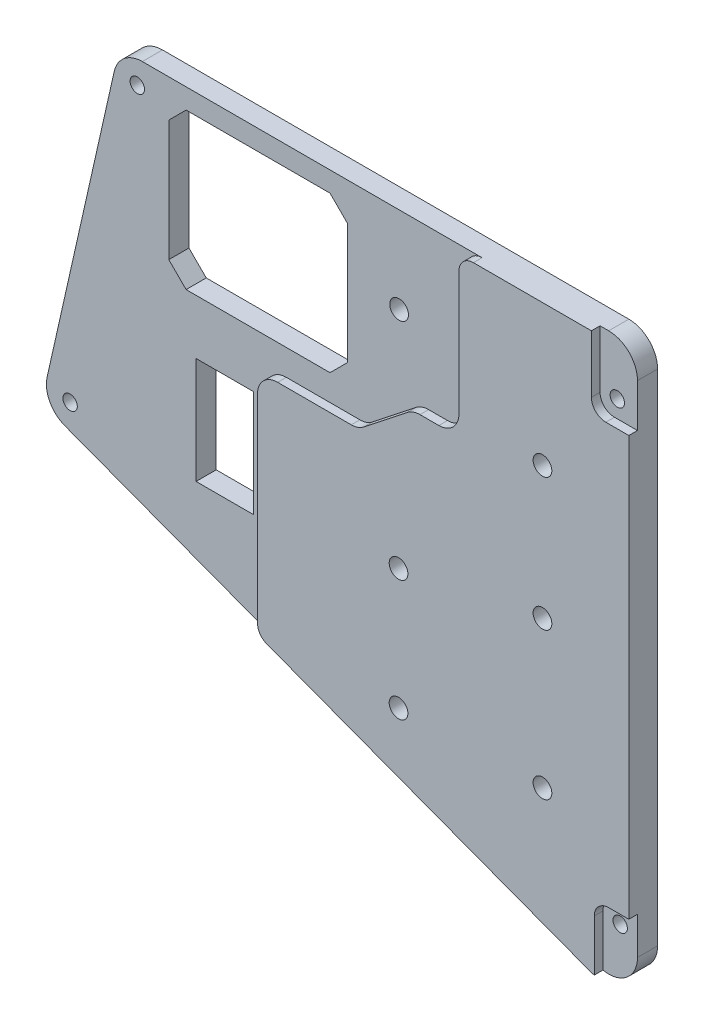
SolidWorks part; units mm, degrees
ref_plane "Front Plane" through (0, 0, 0) normal (0, 0, 1) x (1, 0, 0)
ref_plane "Top Plane" through (0, 0, 0) normal (0, 1, 0) x (1, 0, 0)
ref_plane "Right Plane" through (0, 0, 0) normal (1, 0, 0) x (0, 0, -1)
sketch "Sketch1" plane through (0, 0, 0) normal (0, 0, 1) x (1, 0, 0)
  line L0 (-72.3248, -75.5684) -> (113.0098, -145.4046)
  line L1 (-45.4641, 47.4986) -> (116.5359, 47.4986)
  line L4 (126.5359, 37.4986) -> (126.5359, -136.0469)
  line L5 (-78.5548, -64.0155) -> (-55.2202, 39.6938)
  arc A0 (116.5359, 47.4986) -> (126.5359, 37.4986) centre (116.5359, 37.4986) cw
  arc A1 (126.5359, -136.0469) -> (113.0098, -145.4046) centre (116.5359, -136.0469) cw
  arc A2 (-72.3248, -75.5684) -> (-78.5548, -64.0155) centre (-68.7987, -66.2107) cw
  arc A3 (-45.4641, 47.4986) -> (-55.2202, 39.6938) centre (-45.4641, 37.4986) ccw
  point P5 (126.5359, 47.4986)
  point P9 (126.5359, -150.5014)
  point P14 (-53.4641, 47.4986)
  dimension "D1" = 10
  dimension "D2" = 198
  dimension "D4" = 180
extrude "Boss-Extrude1" add sketch "Sketch1" along normal blind 10
sketch "Sketch2" plane through (0, 0, 10) normal (0, 0, 1) x (1, 0, 0)
  line L0 (116.5359, 47.4986) -> (-45.4641, 47.4986) construction
  line L1 (-26.7987, -32.5014) -> (-6.7987, -32.5014)
  line L2 (-26.7987, -32.5014) -> (-26.7987, -69.5014)
  line L3 (-26.7987, -69.5014) -> (-6.7987, -69.5014)
  line L4 (-6.7987, -32.5014) -> (-6.7987, -69.5014)
  line L5 (126.5359, -136.0469) -> (126.5359, 37.4986) construction
  line L6 (-30.2652, 40.4986) -> (19.7348, 40.4986)
  line L7 (-36.2652, 34.4986) -> (-36.2652, -7.5014)
  line L8 (-30.2652, -13.5014) -> (19.7348, -13.5014)
  line L9 (25.7348, 34.4986) -> (25.7348, -7.5014)
  line L10 (-36.2652, 34.4986) -> (-30.2652, 40.4986)
  line L11 (-36.2652, -7.5014) -> (-30.2652, -13.5014)
  line L12 (19.7348, -13.5014) -> (25.7348, -7.5014)
  line L13 (19.7348, 40.4986) -> (25.7348, 34.4986)
  arc A0 (-78.5548, -64.0155) -> (-72.3248, -75.5684) centre (-68.7987, -66.2107) ccw construction
  circle A1 centre (43.7348, 17.4986) radius 3.25
  circle A2 centre (96.5359, -1.5014) radius 3.25
  circle A3 centre (96.5359, -47.5014) radius 3.25
  circle A4 centre (96.5359, -98.5014) radius 3.25
  circle A5 centre (46.5359, -57.5014) radius 3.25
  circle A6 centre (46.5359, -99.5014) radius 3.25
  point P9 (-36.2652, 40.4986)
  point P10 (25.7348, -13.5014)
  point P11 (-36.2652, -13.5014)
  point P12 (25.7348, 40.4986)
  dimension "D11" = 6.5
  dimension "D18" = 6.5
  dimension "D21" = 6.5
  dimension "D24" = 6.5
  dimension "D27" = 6.5
  dimension "D30" = 6.5
  dimension "D1" = 20
  dimension "D2" = 37
  dimension "D3" = 42
  dimension "D4" = 80
  dimension "D5" = 62
  dimension "D6" = 54
  dimension "D7" = 7
  dimension "D8" = 100.8011
  dimension "D9" = 30
  dimension "D10" = 18
  dimension "D12" = 30
  dimension "D17" = 49
  dimension "D19" = 30
  dimension "D20" = 95
  dimension "D22" = 30
  dimension "D23" = 146
  dimension "D25" = 80
  dimension "D26" = 105
  dimension "D28" = 80
  dimension "D29" = 147
extrude "Cut-Extrude1" cut sketch "Sketch2" against normal blind 10
sketch "Sketch3" plane through (0, 0, 10) normal (0, 0, 1) x (1, 0, 0)
  line L0 (-2.4641, -101.8927) -> (-2.4641, -29.5014)
  line L1 (-72.3248, -75.5684) -> (113.0098, -145.4046) construction
  line L2 (126.5359, -136.0469) -> (126.5359, 37.4986) construction
  line L3 (-30.2652, -13.5014) -> (19.7348, -13.5014) construction
  line L4 (4.5359, -22.5014) -> (30.1058, -22.5014)
  line L5 (34.4433, -20.9955) -> (49.6285, -9.0072)
  line L6 (53.966, -7.5014) -> (60.5359, -7.5014)
  line L7 (67.5359, -0.5014) -> (67.5359, 47.4986)
  line L8 (116.5359, 47.4986) -> (-45.4641, 47.4986) construction
  line L9 (-2.4641, -101.8927) -> (-72.3422, -75.6765)
  line L10 (-78.5855, -64.1179) -> (-55.22, 39.6944)
  line L11 (-55.2202, 39.6938) -> (-53.4635, 47.4986)
  line L12 (-45.4641, 47.4986) -> (67.5359, 47.4986)
  arc A0 (126.5359, 37.4986) -> (116.5359, 47.4986) centre (116.5359, 37.4986) ccw construction
  arc A1 (67.5359, -0.5014) -> (60.5359, -7.5014) centre (60.5359, -0.5014) cw
  arc A2 (53.966, -7.5014) -> (49.6285, -9.0072) centre (53.966, -14.5014) ccw
  arc A3 (34.4433, -20.9955) -> (30.1058, -22.5014) centre (30.1058, -15.5014) cw
  arc A4 (4.5359, -22.5014) -> (-2.4641, -29.5014) centre (4.5359, -29.5014) ccw
  arc A5 (-45.4641, 47.4986) -> (-55.22, 39.6944) centre (-45.4641, 37.4986) ccw
  arc A6 (-78.5855, -64.1179) -> (-72.3422, -75.6765) centre (-68.8296, -66.3137) ccw
  point P19 (67.5359, -7.5014)
  point P22 (51.5359, -7.5014)
  point P25 (32.5359, -22.5014)
  point P28 (-2.4641, -22.5014)
  circle M7 centre (43.7348, 17.4986) radius 3.25
  line M8 (-36.2652, -7.5014) -> (-36.2652, 34.4986)
  line M9 (-36.2652, 34.4986) -> (-30.2652, 40.4986)
  line M10 (-30.2652, 40.4986) -> (19.7348, 40.4986)
  line M11 (19.7348, 40.4986) -> (25.7348, 34.4986)
  line M12 (25.7348, 34.4986) -> (25.7348, -7.5014)
  line M13 (25.7348, -7.5014) -> (19.7348, -13.5014)
  line M14 (19.7348, -13.5014) -> (-30.2652, -13.5014)
  line M15 (-30.2652, -13.5014) -> (-36.2652, -7.5014)
  line M16 (-6.7987, -69.5014) -> (-26.7987, -69.5014)
  line M17 (-26.7987, -69.5014) -> (-26.7987, -32.5014)
  line M18 (-26.7987, -32.5014) -> (-6.7987, -32.5014)
  line M19 (-6.7987, -32.5014) -> (-6.7987, -69.5014)
  line M21 (116.5359, 47.4986) -> (-45.4641, 47.4986)
  arc M22 (-45.4641, 47.4986) -> (-55.2202, 39.6938) centre (-45.4641, 37.4986) ccw
  line M23 (-55.2202, 39.6938) -> (-78.5548, -64.0155)
  arc M24 (-78.5548, -64.0155) -> (-72.3248, -75.5684) centre (-68.7987, -66.2107) ccw
  line M25 (-72.3248, -75.5684) -> (113.0098, -145.4046)
  dimension "D7" = 7
  dimension "D8" = 10
  dimension "D1" = 129
  dimension "D2" = 9
  dimension "D3" = 49
  dimension "D4" = 55
  dimension "D5" = 16
  dimension "D6" = 35
extrude "Cut-Extrude2" cut sketch "Sketch3" against normal blind 3 contours A4 L4 A3 L5 A2 L6 A1 L7 L0 M21 M22 M23 M24 M25 M7 M19 M16 M17 M18 M15 M8 M9 M10 M11 M12 M13 M14
fillet "Fillet1" radius 5 2 edges at (-2.4641, -101.8927, 8.5) (67.5359, 47.4986, 8.5)
sketch "Sketch4" plane through (0, 0, 10) normal (0, 0, 1) x (1, 0, 0)
  line L0 (126.5359, -136.0469) -> (126.5359, 37.4986) construction
  line L1 (126.5359, 22.4986) -> (118.5359, 22.4986)
  line L2 (126.5359, 22.4986) -> (126.5359, 47.4986)
  line L3 (126.5359, 47.4986) -> (113.5359, 47.4986)
  line L4 (113.5359, 27.4986) -> (113.5359, 47.4986)
  line L5 (116.5359, 47.4986) -> (72.5359, 47.4986) construction
  line L7 (126.5359, -123.0469) -> (119.5359, -123.0469)
  line L8 (126.5359, -123.0469) -> (126.5359, -146.0469)
  line L9 (126.5359, -146.0469) -> (114.5359, -146.0469)
  line L10 (114.5359, -128.0469) -> (114.5359, -146.0469)
  arc A0 (118.5359, 22.4986) -> (113.5359, 27.4986) centre (118.5359, 27.4986) cw
  arc A1 (113.0098, -145.4046) -> (126.5359, -136.0469) centre (116.5359, -136.0469) ccw construction
  arc A2 (119.5359, -123.0469) -> (114.5359, -128.0469) centre (119.5359, -128.0469) ccw
  point P10 (113.5359, 22.4986)
  point P20 (114.5359, -123.0469)
  dimension "D3" = 5
  dimension "D7" = 5
  dimension "D1" = 13
  dimension "D2" = 25
  dimension "D4" = 12
  dimension "D5" = 23
  dimension "D6" = 10
extrude "Cut-Extrude3" cut sketch "Sketch4" against normal blind 3
sketch "Sketch5" plane through (0, 0, 7) normal (0, 0, 1) x (1, 0, 0)
  line L0 (114.5359, -128.0469) -> (114.5359, -145.8448) construction
  line L1 (126.5359, -123.0469) -> (119.5359, -123.0469) construction
  line L2 (113.5359, 47.4986) -> (113.5359, 27.4986) construction
  line L3 (118.5359, 22.4986) -> (126.5359, 22.4986) construction
  line L4 (72.5359, 47.4986) -> (-45.4641, 47.4986) construction
  circle A0 centre (120.5359, -129.0469) radius 2.5
  circle A2 centre (119.5359, 28.4986) radius 2.5
  circle A3 centre (-47.2202, 39.4986) radius 2.5
  circle A4 centre (-70.5548, -67.5684) radius 2.5
  dimension "D1" = 5
  dimension "D6" = 5
  dimension "D9" = 5
  dimension "D12" = 5
  dimension "D2" = 6
  dimension "D3" = 6
  dimension "D4" = 6
  dimension "D5" = 6
  dimension "D7" = 8
  dimension "D8" = 8
  dimension "D10" = 8
  dimension "D11" = 8
extrude "Cut-Extrude4" cut sketch "Sketch5" against normal blind 7
